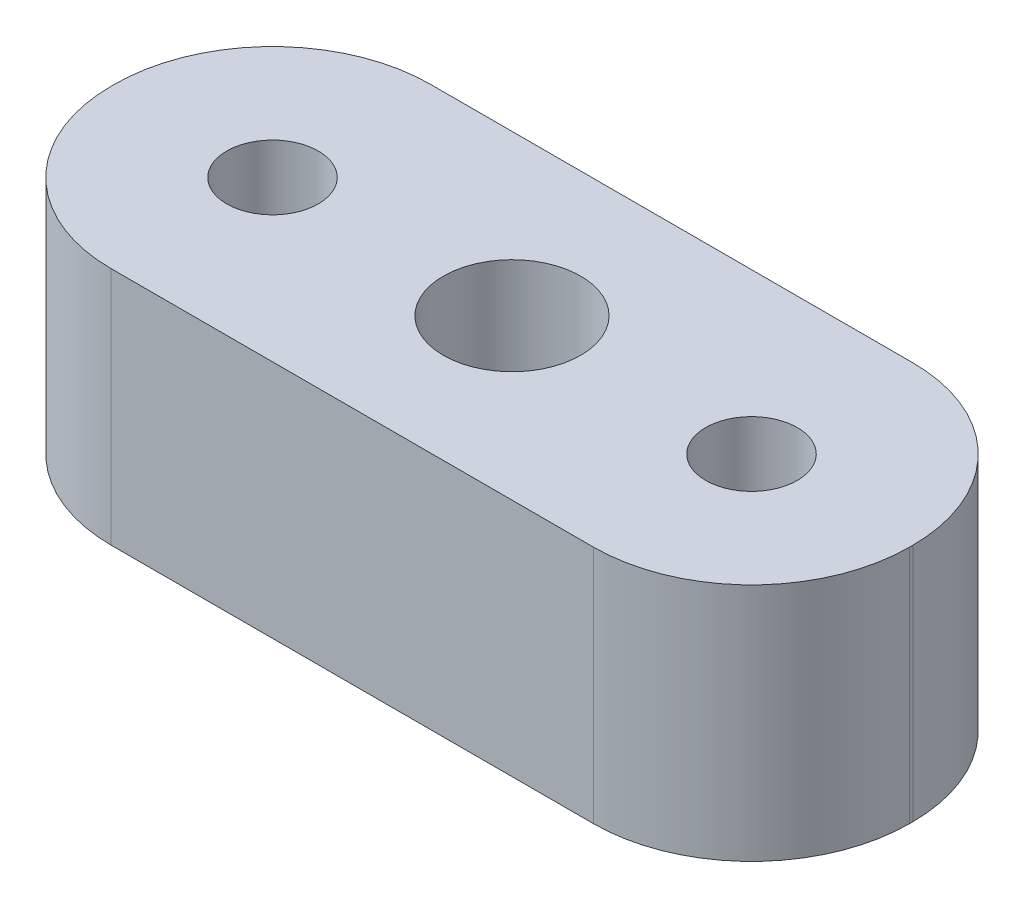
SolidWorks part; units mm, degrees
ref_plane "Front Plane" through (0, 0, 0) normal (0, 0, 1) x (1, 0, 0)
ref_plane "Top Plane" through (0, 0, 0) normal (0, 1, 0) x (1, 0, 0)
ref_plane "Right Plane" through (0, 0, 0) normal (1, 0, 0) x (0, 0, -1)
sketch "Sketch1" plane through (0, 0, 0) normal (0, 1, 0) x (1, 0, 0)
  line L0 (0, 0) -> (0, -1.8253) construction
  line L1 (-1.51, 1) -> (1.51, 1)
  line L2 (-2.5, 0.01) -> (-2.5, -0.01)
  line L3 (-1.51, -1) -> (1.51, -1)
  line L4 (2.5, 0.01) -> (2.5, -0.01)
  line L5 (0, 0) -> (-5.0107, 0) construction
  circle A0 centre (0, 0) radius 0.43
  circle A1 centre (1.5, 0) radius 0.287
  circle A2 centre (-1.5, 0) radius 0.287
  arc A4 (1.51, -1) -> (2.5, -0.01) centre (1.51, -0.01) ccw
  arc A5 (2.5, 0.01) -> (1.51, 1) centre (1.51, 0.01) ccw
  arc A6 (-1.51, -1) -> (-2.5, -0.01) centre (-1.51, -0.01) cw
  arc A7 (-2.5, 0.01) -> (-1.51, 1) centre (-1.51, 0.01) cw
  point P19 (-2.5, -1)
  point P22 (-2.5, 1)
  dimension "D1" = 0.99
  dimension "D2" = 1
  dimension "D4" = 2
  dimension "D6" = 1
extrude "Boss-Extrude1" add sketch "Sketch1" along normal blind 1.5
